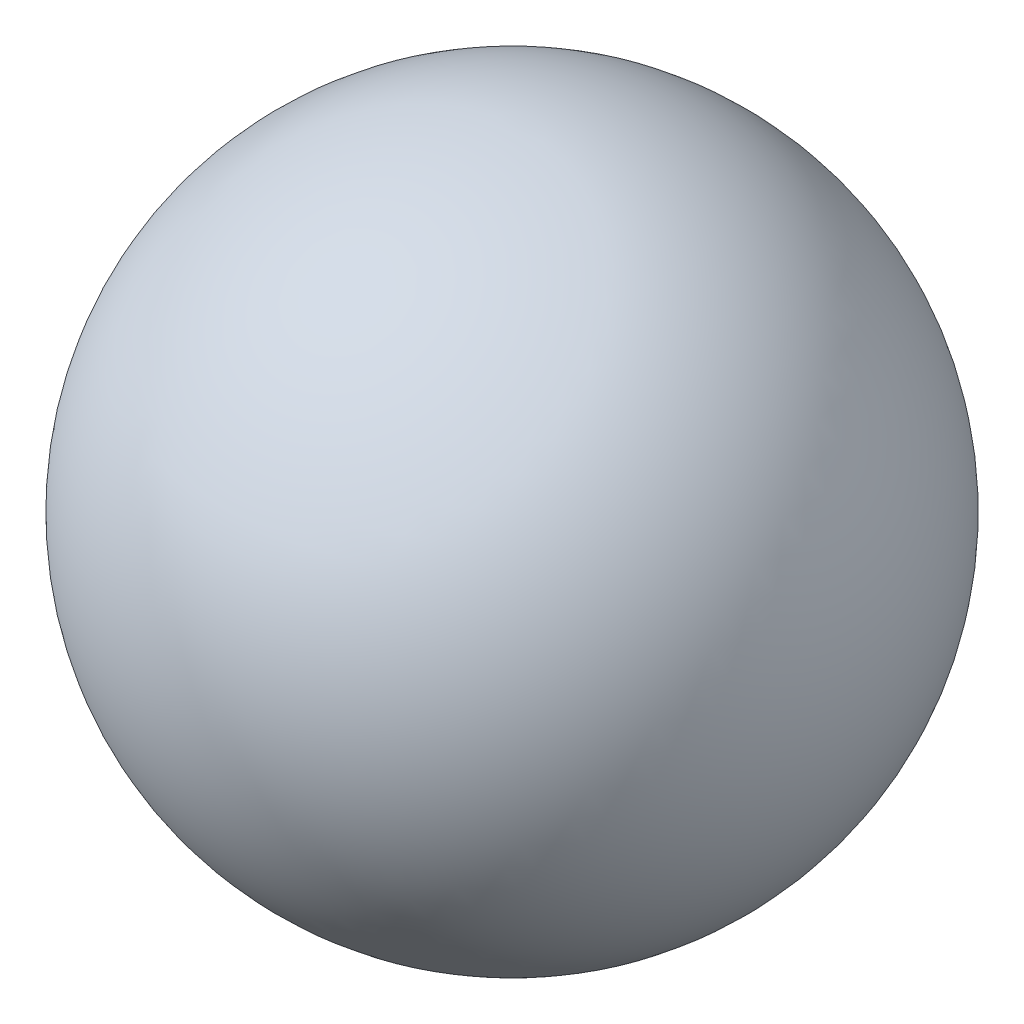
SolidWorks part; units mm, degrees
ref_plane "前视基准面" through (0, 0, 0) normal (0, 0, 1) x (1, 0, 0)
ref_plane "上视基准面" through (0, 0, 0) normal (0, 1, 0) x (1, 0, 0)
ref_plane "右视基准面" through (0, 0, 0) normal (1, 0, 0) x (0, 0, -1)
sketch "草图1" plane through (0, 0, 0) normal (0, 0, 1) x (1, 0, 0)
  line L0 (0, 21) -> (0, -21) construction
  line L1 (0, 21) -> (0, -21)
  arc A0 (0, 21) -> (0, -21) centre (0, 0) ccw
  dimension "D1" = 42
revolve "旋转4" add sketch "草图1" angle 360 about L1
